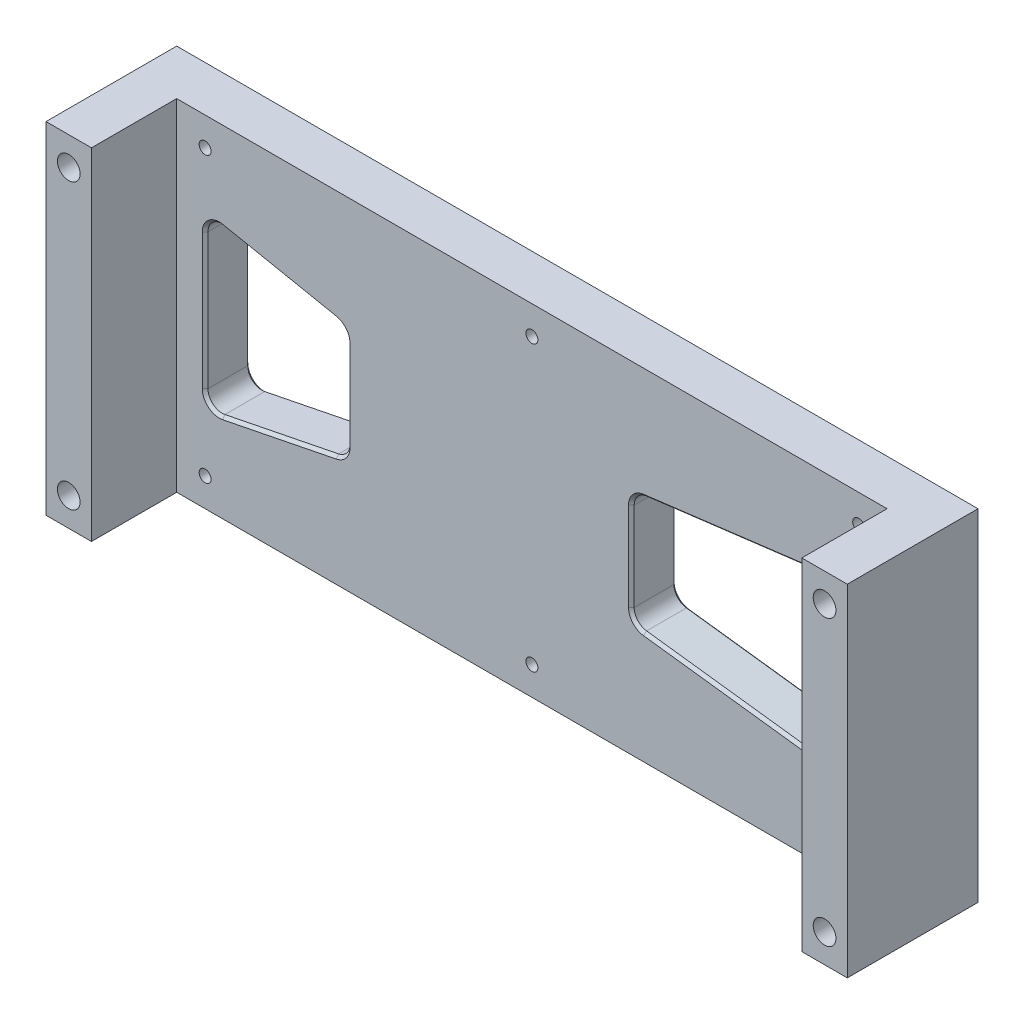
SolidWorks part; units mm, degrees
material "6063-T4"
ref_plane "Front Plane" through (0, 0, 0) normal (0, 0, 1) x (1, 0, 0)
ref_plane "Top Plane" through (0, 0, 0) normal (0, 1, 0) x (1, 0, 0)
ref_plane "Right Plane" through (0, 0, 0) normal (1, 0, 0) x (0, 0, -1)
curve "Curve1"
  spline degree 3 poles (175, 0, 0.3867) (172.0852, 0, 1.0897) (166.2646, 0, 2.4935) (154.6086, 0, 5.0979) (140.0385, 0, 8.0953) (122.5354, 0, 11.2849) (105.0361, 0, 14.0542) (87.5366, 0, 16.3202) (70.0311, 0, 17.9237) (55.4199, 0, 18.4971) (43.7404, 0, 18.2662) (34.9711, 0, 17.6609) (26.1801, 0, 16.4891) (18.8666, 0, 14.8537) (13.0417, 0, 12.9094) (8.568, 0, 10.9324) (4.8344, 0, 8.5605) (1.3476, 0, 5.1921) (-0.8977, 0, 0) (1.3476, 0, -5.1921) (4.8344, 0, -8.5605) (8.568, 0, -10.9324) (13.0417, 0, -12.9094) (18.8666, 0, -14.8537) (26.1801, 0, -16.4891) (34.9711, 0, -17.6609) (43.7404, 0, -18.2662) (55.4199, 0, -18.4971) (70.0311, 0, -17.9237) (87.5366, 0, -16.3202) (105.0361, 0, -14.0542) (122.5354, 0, -11.2849) (140.0385, 0, -8.0953) (154.6086, 0, -5.0979) (166.2646, 0, -2.4935) (172.0852, 0, -1.0897) (175, 0, -0.3867) knots 0 0 0 0 0.024528 0.048982 0.097703 0.146209 0.194518 0.242628 0.290539 0.338289 0.362155 0.386077 0.410161 0.434654 0.447248 0.460338 0.47462 0.483093 0.5 0.516907 0.52538 0.539662 0.552752 0.565346 0.589839 0.613923 0.637845 0.661711 0.709461 0.757372 0.805482 0.853791 0.902297 0.951018 0.975472 1 1 1 1
sketch "Sketch1" plane through (0, 0, 0) normal (0, 1, 0) x (1, 0, 0)
  line L0 (0, 0) -> (-36, 0)
  line L1 (175, 0.3867) -> (175, -0.3867) construction
  line L2 (-36, 0) -> (-36, 46)
  line L3 (-36, 46) -> (246, 46)
  line L4 (246, 46) -> (246, 0)
  line L5 (-36, 0) -> (-36, 5)
  line L6 (246, 0) -> (246, 5)
  line L7 (-36, 5) -> (1.6146, 5)
  line L8 (246, 5) -> (154.8787, 5)
  line L9 (246, 0) -> (175, 0)
  line L11 (246, 46) -> (-36, 46)
  line L12 (246, 46) -> (246, 30)
  line L13 (246, 30) -> (-36, 30)
  line L14 (-36, 46) -> (-36, 30)
  arc A0 (175, 0.3867) -> (175, -0.3867) centre (174.9067, 0) cw
  spline S0 degree 3 poles (991.754, -1812.021) (410.0199, 103.4385) (290.9339, 25.363) (154.6086, -5.0979) (140.0385, -8.0953) (122.5354, -11.2849) (105.0361, -14.0542) (87.5366, -16.3202) (70.0311, -17.9237) (55.4199, -18.4971) (43.7404, -18.2662) (34.9711, -17.6609) (26.1801, -16.4891) (18.8666, -14.8537) (13.0417, -12.9094) (8.568, -10.9324) (4.8344, -8.5605) (1.3476, -5.1921) (-0.8977, 0) (1.3476, 5.1921) (4.8344, 8.5605) (8.568, 10.9324) (13.0417, 12.9094) (18.8666, 14.8537) (26.1801, 16.4891) (34.9711, 17.6609) (43.7404, 18.2662) (55.4199, 18.4971) (70.0311, 17.9237) (87.5366, 16.3202) (105.0361, 14.0542) (122.5354, 11.2849) (140.0385, 8.0953) (154.6086, 5.0979) (290.9339, -25.363) (410.0199, -103.4385) (991.754, 1812.0209) knots -1.045008 -1.045008 -1.045008 -1.045008 0.024528 0.048982 0.097703 0.146209 0.194518 0.242628 0.290539 0.338289 0.362155 0.386077 0.410161 0.434654 0.447248 0.460338 0.47462 0.483093 0.5 0.516907 0.52538 0.539662 0.552752 0.565346 0.589839 0.613923 0.637845 0.661711 0.709461 0.757372 0.805482 0.853791 0.902297 0.951018 0.975472 2.045008 2.045008 2.045008 2.045008 only from (175, -0.3867) to (175, 0.3867) construction
  spline S1 degree 3 poles (175, -0.3867) (172.0852, -1.0897) (166.2646, -2.4935) (154.6086, -5.0979) (140.0385, -8.0953) (122.5354, -11.2849) (105.0361, -14.0542) (87.5366, -16.3202) (70.0311, -17.9237) (55.4199, -18.4971) (43.7404, -18.2662) (34.9711, -17.6609) (26.1801, -16.4891) (18.8666, -14.8537) (13.0417, -12.9094) (8.568, -10.9324) (4.8344, -8.5605) (1.3476, -5.1921) (-0.8977, 0) (1.3476, 5.1921) (4.8344, 8.5605) (8.568, 10.9324) (13.0417, 12.9094) (18.8666, 14.8537) (26.1801, 16.4891) (34.9711, 17.6609) (43.7404, 18.2662) (55.4199, 18.4971) (70.0311, 17.9237) (87.5366, 16.3202) (105.0361, 14.0542) (122.5354, 11.2849) (140.0385, 8.0953) (154.6086, 5.0979) (166.2646, 2.4935) (172.0852, 1.0897) (175, 0.3867) knots 0 0 0 0 0.024528 0.048982 0.097703 0.146209 0.194518 0.242628 0.290539 0.338289 0.362155 0.386077 0.410161 0.434654 0.447248 0.460338 0.47462 0.483093 0.5 0.516907 0.52538 0.539662 0.552752 0.565346 0.589839 0.613923 0.637845 0.661711 0.709461 0.757372 0.805482 0.853791 0.902297 0.951018 0.975472 1 1 1 1
  point P15 (175, 0)
  dimension "D6" = 16
  dimension "D1" = 46
  dimension "D2" = 36
  dimension "D3" = 282
  dimension "D4" = 5
  dimension "D5" = 5
extrude "Boss-Extrude1" add sketch "Sketch1" along normal blind 120 contours L13 L4 L3 L2
sketch "Sketch4" plane through (0, 0, -30) normal (0, 0, 1) x (1, 0, 0)
  line L0 (246, 0) -> (-36, 0) construction
  line L1 (-36, 120) -> (-20, 120)
  line L2 (-36, 120) -> (-36, 0)
  line L3 (-36, 0) -> (-20, 0)
  line L4 (-20, 120) -> (-20, 0)
  line L6 (246, 120) -> (230, 120)
  line L7 (246, 120) -> (246, 0)
  line L8 (246, 0) -> (230, 0)
  line L9 (230, 120) -> (230, 0)
  dimension "D1" = 16
  dimension "D2" = 16
extrude "Boss-Extrude2" add sketch "Sketch4" along normal blind 30
sketch "Sketch2" plane through (0, 0, -46) normal (0, 0, 1) x (1, 0, 0)
  line L0 (246, 120) -> (246, 0) construction
  line L1 (-36, 120) -> (-28, 120) construction
  line L2 (-36, 120) -> (-36, 110) construction
  line L3 (-36, 110) -> (-28, 110) construction
  line L4 (-28, 120) -> (-28, 110) construction
  line L5 (-36, 0) -> (-28, 0) construction
  line L6 (-36, 0) -> (-36, 10) construction
  line L7 (-36, 10) -> (-28, 10) construction
  line L8 (-28, 0) -> (-28, 10) construction
  line L9 (246, 120) -> (238, 120) construction
  line L10 (246, 120) -> (246, 110) construction
  line L11 (246, 110) -> (238, 110) construction
  line L12 (238, 120) -> (238, 110) construction
  line L13 (-36, 0) -> (246, 0) construction
  line L14 (238, 10) -> (246, 10) construction
  line L15 (238, 10) -> (238, 0) construction
  line L16 (238, 0) -> (246, 0) construction
  line L17 (246, 10) -> (246, 0) construction
  circle A0 centre (-28, 110) radius 4
  circle A1 centre (-28, 10) radius 4
  circle A2 centre (238, 110) radius 4
  circle A3 centre (238, 10) radius 4
  dimension "D1" = 8
  dimension "D2" = 10
  dimension "D3" = 10
  dimension "D4" = 8
  dimension "D5" = 8
  dimension "D6" = 10
  dimension "D7" = 8
  dimension "D8" = 10
extrude "Cut-Extrude1" cut sketch "Sketch2" along normal through all contours A2 | A0 | A1 | A3
sketch "Sketch3" plane through (0, 0, -46) normal (0, 0, -1) x (-1, 0, 0)
  line L0 (-90, 60) -> (36, 60) construction
  line L1 (-90, 60) -> (-90, 25.42) construction
  line L2 (-55, 51) -> (-75, 51)
  line L3 (36, 120) -> (36, 0) construction
  line L4 (-55, 51) -> (-55, 69)
  line L5 (-55, 69) -> (-75, 69)
  line L6 (-75, 51) -> (-75, 69)
  line L7 (-105, 51) -> (-105, 69)
  line L8 (-125, 69) -> (-105, 69)
  line L9 (-125, 51) -> (-125, 69)
  line L10 (-125, 51) -> (-105, 51)
  circle A0 centre (-90, 60) radius 8
  point P6 (-87.5, 60)
  point P10 (-55, 60)
  dimension "D1" = 18
  dimension "D2" = 20
  dimension "D3" = 0
  dimension "D4" = 35
  dimension "D5" = 126
sketch "Sketch5" plane through (0, 0, -30) normal (0, 0, 1) x (1, 0, 0)
  line L0 (230, 120) -> (-20, 120) construction
  line L1 (-10, 10) -> (220, 10) construction
  line L2 (-10, 10) -> (-10, 110) construction
  line L3 (-10, 110) -> (220, 110) construction
  line L4 (220, 10) -> (220, 110) construction
  line L5 (230, 0) -> (-20, 0) construction
  line L6 (-20, 0) -> (-20, 120) construction
  line L7 (230, 120) -> (230, 0) construction
  dimension "D1" = 10
  dimension "D2" = 10
  dimension "D3" = 10
  dimension "D4" = 10
hole_wizard "M5 Tapped Hole1" positions "Sketch6" profile "Sketch7" tap size "M5" standard "ISO" end condition through all
sketch "Sketch6" plane through (0, 0, -30) normal (0, 0, 1) x (1, 0, 0)
  line L0 (-10, 110) -> (220, 110) construction
  line L1 (-10, 10) -> (220, 10) construction
  point P0 (-10, 110)
  point P3 (105, 110)
  point P7 (220, 110)
  point P10 (220, 10)
  point P13 (105, 10)
  point P17 (-10, 10)
sketch "Sketch7" plane through (-10, 110, -30) normal (1, 0, 0) x (0, -1, 0)
  line L0 (0, 0) -> (0, 16)
  line L1 (0, 16) -> (2.1, 16)
  line L2 (2.1, 16) -> (2.1, 0)
  line L5 (2.1, 0) -> (0, 0)
  line L11 (0, -6.35) -> (0, 107.95) construction
  dimension "Thru Tap Drill Dia." = 4.2
  dimension "Thru Tap Drill Depth" = 16
cosmetic thread "Hole Thread1" parameters "D2"=5
cosmetic thread "Hole Thread2" parameters "D2"=5
cosmetic thread "Hole Thread3" parameters "D2"=5
cosmetic thread "Hole Thread4" parameters "D2"=5
cosmetic thread "Hole Thread5" parameters "D2"=5
cosmetic thread "Hole Thread6" parameters "D2"=5
hole_wizard "Tap Drill for M6 Tap1" positions "Sketch9" profile "Sketch10" hole size "M6" standard "ISO"
sketch "Sketch9" plane through (0, 0, -46) normal (0, 0, -1) x (-1, 0, 0)
  point P0 (-55, 51)
  point P9 (-55, 69)
  point P34 (-125, 69)
  point P37 (-125, 51)
sketch "Sketch10" plane through (55, 51, -46) normal (1, 0, 0) x (0, 1, 0)
  line L0 (0, 0) -> (0, 9.5022)
  line L1 (0, 9.5022) -> (2.5, 8)
  line L2 (2.5, 8) -> (2.5, 0)
  line L5 (2.5, 0) -> (0, 0)
  line L10 (0, 9.5022) -> (-2.5, 8) construction
  line L11 (0, -6.35) -> (0, 107.95) construction
  dimension "Hole Dia." = 5
  dimension "Hole Depth" = 8
  dimension "Drill Angle" = 118
sketch "Sketch11" plane through (0, 0, -46) normal (0, 0, -1) x (-1, 0, 0)
  line L0 (-140, 75.5861) -> (-140, 44.4139)
  line L1 (-144.3798, 39.4525) -> (-214.3798, 30.7025)
  line L2 (-220, 35.6639) -> (-220, 84.3361)
  line L3 (-214.3798, 89.2975) -> (-144.3798, 80.5475)
  line L4 (-230, 120) -> (-230, 0) construction
  line L5 (-230, 0) -> (20, 0) construction
  line L6 (-230, 120) -> (20, 120) construction
  line L7 (10, 83.901) -> (10, 36.099)
  line L8 (10, 10) -> (10, 110) construction
  line L9 (4.0194, 31.1961) -> (-35.9806, 39.1961)
  line L10 (-40, 44.099) -> (-40, 75.901)
  line L11 (-35.9806, 80.8039) -> (4.0194, 88.8039)
  line L12 (-175, 0) -> (0, 0) construction
  line L13 (20, 0) -> (20, 120) construction
  arc A0 (-140, 44.4139) -> (-144.3798, 39.4525) centre (-145, 44.4139) cw
  arc A1 (-214.3798, 30.7025) -> (-220, 35.6639) centre (-215, 35.6639) cw
  arc A2 (-220, 84.3361) -> (-214.3798, 89.2975) centre (-215, 84.3361) cw
  arc A3 (-140, 75.5861) -> (-144.3798, 80.5475) centre (-145, 75.5861) ccw
  arc A4 (10, 36.099) -> (4.0194, 31.1961) centre (5, 36.099) cw
  arc A5 (-35.9806, 39.1961) -> (-40, 44.099) centre (-35, 44.099) cw
  arc A6 (-40, 75.901) -> (-35.9806, 80.8039) centre (-35, 75.901) cw
  arc A7 (10, 83.901) -> (4.0194, 88.8039) centre (5, 83.901) ccw
  point P12 (-140, 40)
  point P15 (-220, 30)
  point P18 (-220, 90)
  point P21 (-140, 80)
  point P34 (10, 30)
  point P37 (-40, 40)
  point P40 (-40, 80)
  point P43 (10, 90)
  dimension "D7" = 5
  dimension "D13" = 5
  dimension "D1" = 10
  dimension "D2" = 90
  dimension "D3" = 30
  dimension "D4" = 30
  dimension "D5" = 40
  dimension "D6" = 40
  dimension "D8" = 30
  dimension "D9" = 40
  dimension "D10" = 40
  dimension "D11" = 30
  dimension "D12" = 60
extrude "Cut-Extrude2" cut sketch "Sketch11" against normal through all
chamfer "Chamfer1" distance 1 angle 45 32 edges at (15.9806, 84.8039, -46) (38.8667, 79.0709, -46) (-8.1699, 87.7677, -46) (40, 60, -46) (-10, 60, -46) (38.8667, 40.9291, -46) (-8.1699, 32.2323, -46) (15.9806, 35.1961, -46) (15.9806, 84.8039, -30) (-8.1699, 87.7677, -30) (38.8667, 79.0709, -30) (-10, 60, -30) (40, 60, -30) (-8.1699, 32.2323, -30) (38.8667, 40.9291, -30) (15.9806, 35.1961, -30) (179.3798, 84.9225, -46) (218.309, 88.0845, -46) (141.2516, 78.8951, -46) (220, 60, -46) (140, 60, -46) (218.309, 31.9155, -46) (141.2516, 41.1049, -46) (179.3798, 35.0775, -46) (179.3798, 84.9225, -30) (141.2516, 78.8951, -30) (218.309, 88.0845, -30) (140, 60, -30) (220, 60, -30) (141.2516, 41.1049, -30) (218.309, 31.9155, -30) (179.3798, 35.0775, -30)
